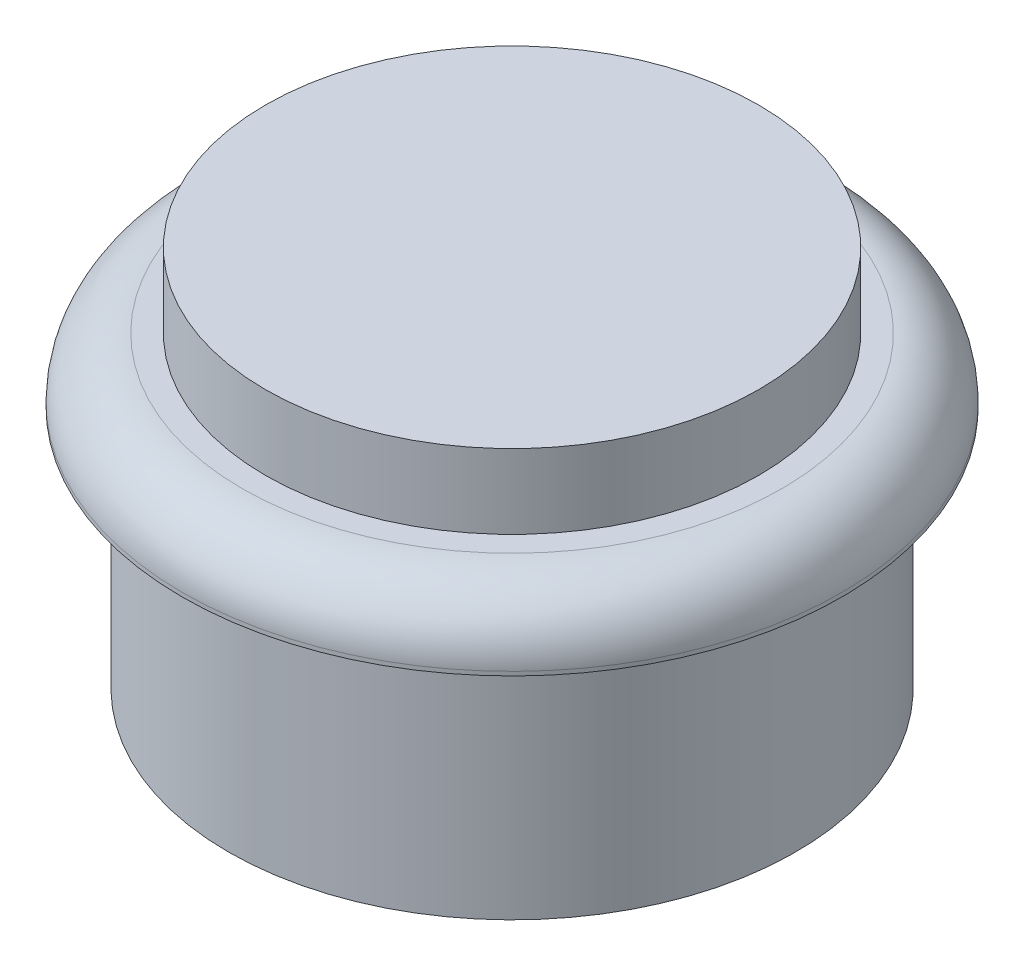
SolidWorks part; units mm, degrees
ref_plane "Front Plane" through (0, 0, 0) normal (0, 0, 1) x (1, 0, 0)
ref_plane "Top Plane" through (0, 0, 0) normal (0, 1, 0) x (1, 0, 0)
ref_plane "Right Plane" through (0, 0, 0) normal (1, 0, 0) x (0, 0, -1)
sketch "Sketch1" plane through (0, 0, 0) normal (0, 1, 0) x (1, 0, 0)
  circle A0 centre (0, 0) radius 14.2
  dimension "D1" = 28.4
extrude "Boss-Extrude1" add sketch "Sketch1" against normal blind 12.2
sketch "Sketch2" plane through (0, 0, 0) normal (0, 1, 0) x (1, 0, 0)
  circle A0 centre (0, 0) radius 16.5
  dimension "D1" = 33
extrude "Boss-Extrude2" add sketch "Sketch2" along normal blind 3.2
fillet "Fillet1" radius 3 1 edges at (0, 3.2, 16.5)
sketch "Sketch3" plane through (0, 3.2, 0) normal (0, 1, 0) x (1, 0, 0)
  circle A0 centre (0, 0) radius 12.345
  dimension "D1" = 24.69
extrude "Boss-Extrude3" add sketch "Sketch3" along normal blind 3.72
